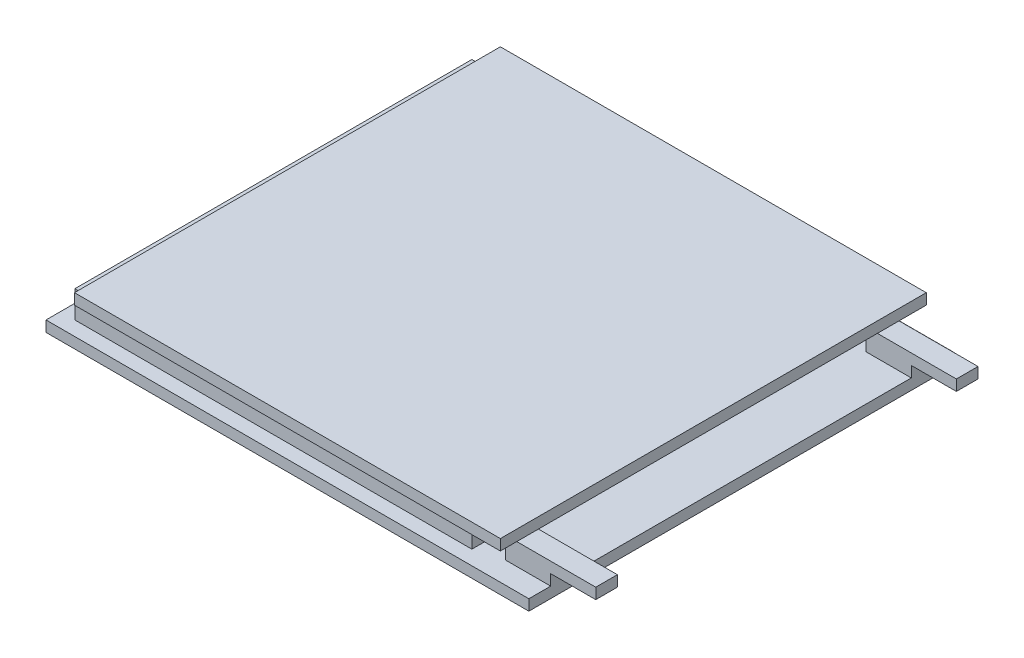
SolidWorks part; units mm, degrees
ref_plane "front" through (0, 0, 0) normal (0, 0, 1) x (1, 0, 0)
ref_plane "top" through (0, 0, 0) normal (0, 1, 0) x (1, 0, 0)
ref_plane "right" through (0, 0, 0) normal (1, 0, 0) x (0, 0, -1)
sketch "Sketch1" plane through (0, 0, 0) normal (0, 1, 0) x (1, 0, 0)
  line L1 (-17.0053, 14.9987) -> (17.0053, 14.9987)
  line L2 (-17.0053, 14.9987) -> (-17.0053, -14.9987)
  line L3 (-17.0053, -14.9987) -> (17.0053, -14.9987)
  line L4 (17.0053, 14.9987) -> (17.0053, -14.9987)
  line L5 (12.9921, 14.9987) -> (-17.0053, -14.9987) construction
  point P4 (0, 14.9987)
  point P5 (17.0053, 0)
  dimension "D1" = 29.9974
  dimension "D2" = 34.0106
  dimension "D3" = 29.9974
extrude "Extrude1" add sketch "Sketch1" against normal blind 0.762
sketch "Sketch2" plane through (0, 0, 0) normal (0, 1, 0) x (-1, 0, 0)
  line L0 (-11.9761, -13.9827) -> (15.9893, 13.9827) construction
  line L1 (-11.9761, 13.9827) -> (15.9893, 13.9827)
  line L2 (-11.9761, 13.9827) -> (-11.9761, -13.9827)
  line L3 (-11.9761, -13.9827) -> (15.9893, -13.9827)
  line L4 (15.9893, 13.9827) -> (15.9893, -13.9827)
  line L5 (17.0053, -14.9987) -> (17.0053, 14.9987) construction
  line L6 (17.0053, 14.9987) -> (-17.0053, 14.9987) construction
  point P9 (2.0066, 0)
  dimension "D1" = 1.016
  dimension "D2" = 1.016
extrude "Extrude2" add sketch "Sketch2" along normal blind 1.905
sketch "Sketch3" plane through (0, 1.905, 0) normal (0, 1, 0) x (-1, 0, 0)
  line L0 (-14.9987, -14.9987) -> (14.9987, 14.9987) construction
  line L1 (14.9987, -14.9987) -> (-14.9987, -14.9987)
  line L2 (14.9987, -14.9987) -> (14.9987, 14.9987)
  line L3 (14.9987, 14.9987) -> (-14.9987, 14.9987)
  line L4 (-14.9987, -14.9987) -> (-14.9987, 14.9987)
  dimension "D1" = 29.9974
extrude "Extrude3" add sketch "Sketch3" along normal blind 0.762
sketch "Sketch4" plane through (0, 0, 0) normal (0, 0, 1) x (1, 0, 0)
  line L0 (13.8303, 0) -> (13.8303, 1.524)
  line L1 (13.8303, 1.524) -> (20.1803, 1.524)
  line L2 (20.1803, 1.524) -> (20.1803, 0.762)
  line L3 (20.1803, 0.762) -> (17.0053, 0.762)
  line L4 (17.0053, 0.762) -> (17.0053, 0)
  line L5 (17.0053, 0) -> (13.8303, 0)
  line L6 (-17.0053, 0) -> (17.0053, 0) construction
  line L7 (17.0053, -0.762) -> (17.0053, 0) construction
  dimension "D1" = 1.524
  dimension "D2" = 3.175
  dimension "D3" = 0.762
  dimension "D4" = 6.35
extrude "Extrude4" add sketch "Sketch4" along normal mid plane 1.524 from offset 12.7
mirror "Mirror1" about plane through (0, 0, 0) normal (0, 0, 1) of "Extrude4"
